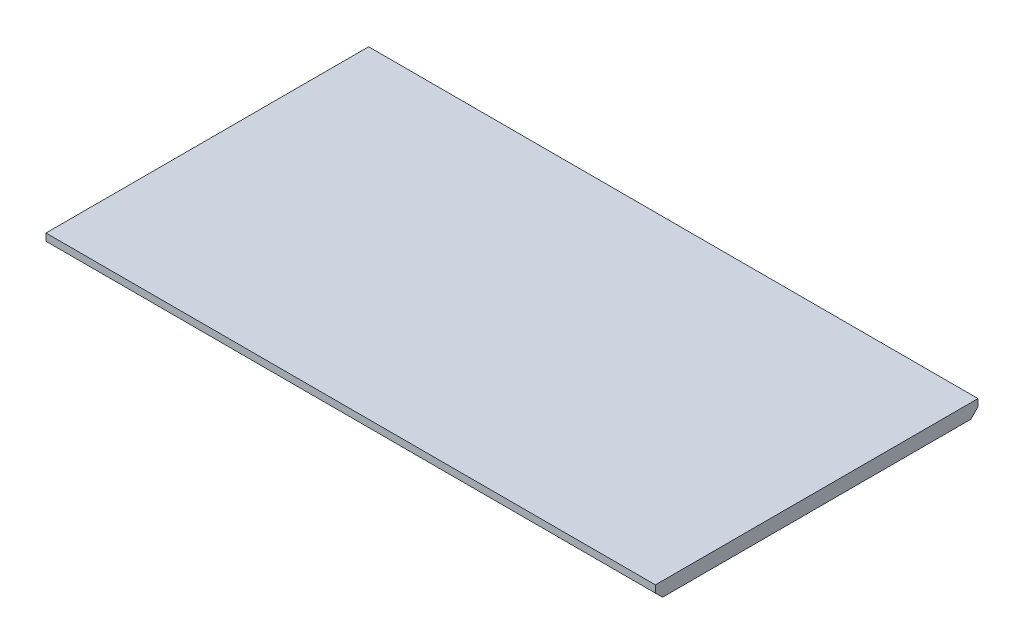
SolidWorks part; units mm, degrees
ref_plane "Front" through (0, 0, 0) normal (0, 0, 1) x (1, 0, 0)
ref_plane "Top" through (0, 0, 0) normal (0, 1, 0) x (1, 0, 0)
ref_plane "Right" through (0, 0, 0) normal (1, 0, 0) x (0, 0, -1)
sketch "草图1" plane through (0, 0, 0) normal (0, 1, 0) x (1, 0, 0)
  line L1 (-42.5, -22.5) -> (42.5, -22.5)
  line L2 (-42.5, -22.5) -> (-42.5, 22.5)
  line L3 (-42.5, 22.5) -> (42.5, 22.5)
  line L4 (42.5, -22.5) -> (42.5, 22.5)
  line L5 (-42.5, -22.5) -> (42.5, 22.5) construction
  line L6 (-42.5, 22.5) -> (42.5, -22.5) construction
  point P0 (0, 0)
  dimension "D1" = 85
  dimension "D2" = 45
extrude "凸台-拉伸1" add sketch "草图1" along normal blind 2
chamfer "倒角1" distance 1 angle 45 2 edges at (0, 0, -22.5) (0, 0, 22.5)
